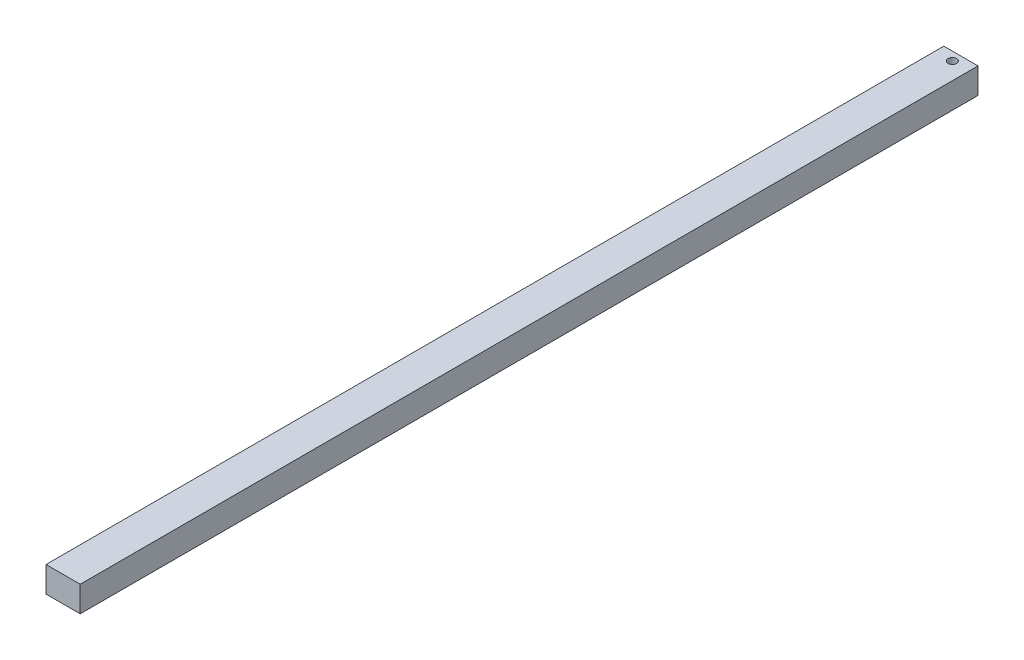
SolidWorks part; units mm, degrees
ref_plane "前视基准面" through (0, 0, 0) normal (0, 0, 1) x (1, 0, 0)
ref_plane "上视基准面" through (0, 0, 0) normal (0, 1, 0) x (1, 0, 0)
ref_plane "右视基准面" through (0, 0, 0) normal (1, 0, 0) x (0, 0, -1)
other "Configuration Table"
sketch "草图1" plane through (0, 0, 0) normal (0, 1, 0) x (1, 0, 0)
  line L1 (-20, 525) -> (20, 525)
  line L2 (-20, 525) -> (-20, -525)
  line L3 (-20, -525) -> (20, -525)
  line L4 (20, 525) -> (20, -525)
  line L5 (0, -525) -> (0, 525) construction
  line L6 (-20, 0) -> (20, 0) construction
  circle A0 centre (0, 515) radius 5
  point P0 (0, 0)
  dimension "D3" = 10
  dimension "D1" = 40
  dimension "D2" = 1050
  dimension "D4" = 10
extrude "凸台-拉伸1" add sketch "草图1" along normal blind 30
sketch "草图2" plane through (20, 0, 0) normal (1, 0, 0) x (0, 0, -1)
  line L0 (0, 30) -> (0, -103.2917) construction
  line L1 (-525, 30) -> (525, 30) construction
  circle A0 centre (0, 25) radius 3
  dimension "D1" = 6
  dimension "D2" = 5
sketch "草图3" plane through (0, 30, 0) normal (0, 1, 0) x (1, 0, 0)
  line L0 (0.0085, 0) -> (15.0085, 0) construction
  line L1 (-5, 0) -> (-5, -23.4868) construction
  line L2 (-20, 525) -> (-20, -525) construction
  circle A0 centre (-14.5, -3.5) radius 2.5
  circle A1 centre (4.5, -3.5) radius 2.5
  circle A2 centre (-14.5, 3.5) radius 2.5
  circle A3 centre (4.5, 3.5) radius 2.5
  dimension "D1" = 5
  dimension "D4" = 19
  dimension "D5" = 14.9164
  dimension "D2" = 14.9164
  dimension "D3" = 5.5
sketch "草图4" plane through (0, 0, 0) normal (0, -1, 0) x (1, 0, 0)
  line L1 (-10, 10) -> (10, 10)
  line L2 (-10, 10) -> (-10, -10)
  line L3 (-10, -10) -> (10, -10)
  line L4 (10, 10) -> (10, -10)
  line L5 (0, -10) -> (0, 10) construction
  line L6 (-10, 0) -> (10, 0) construction
  point P0 (0, 0)
  dimension "D1" = 20
  dimension "D2" = 20
extrude "切除-拉伸1" cut sketch "草图4" against normal blind 15
ref_plane "基准面2" through (0, 0, 10) normal (0, 0, -1) x (-1, 0, 0)
sketch "草图6" plane through (0, 0, 10) normal (0, 0, -1) x (-1, 0, 0)
  line L3 (-20, 0) -> (20, 0) construction
  line L4 (-20, 30) -> (-20, -103.2917) construction
  circle A0 centre (-5, 5.5) radius 3
  dimension "D2" = 6
  dimension "D3" = 15
  dimension "D1" = 5.5
extrude "切除-拉伸2" cut sketch "草图6" against normal blind 20
